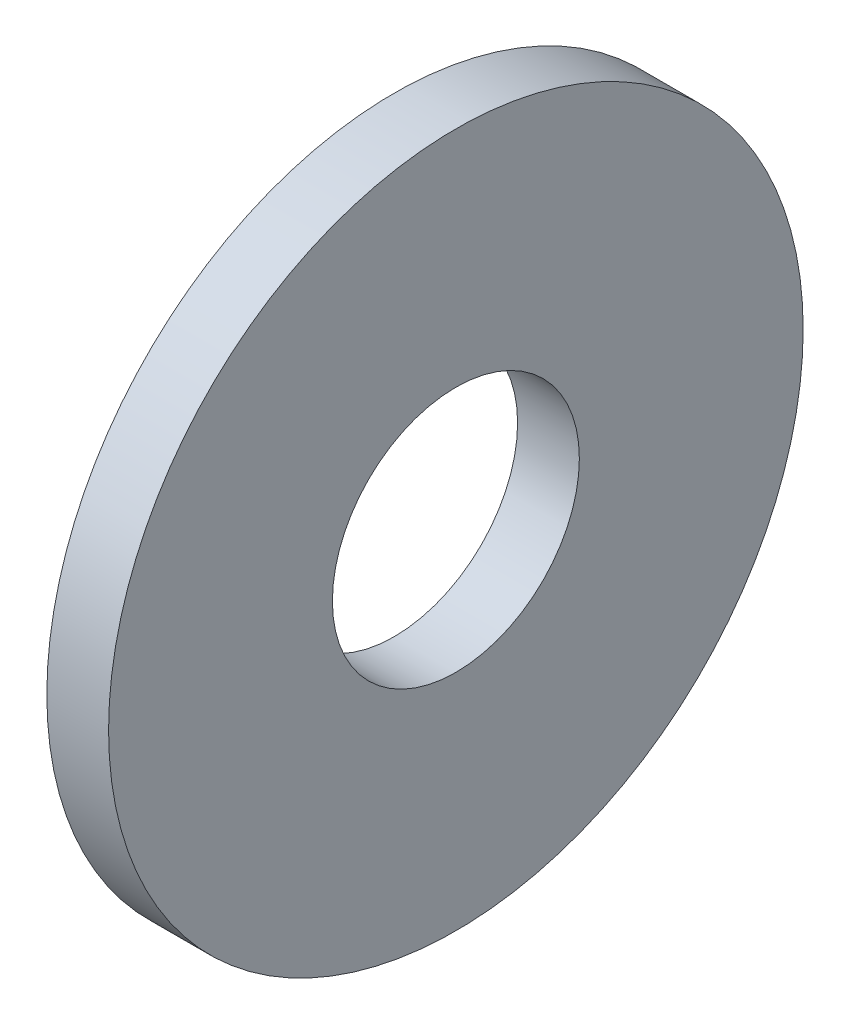
SolidWorks part; units mm, degrees
ref_plane "Plane1" through (0, 0, 0) normal (0, 0, 1) x (1, 0, 0)
ref_plane "Plane2" through (0, 0, 0) normal (0, 1, 0) x (1, 0, 0)
ref_plane "Plane3" through (0, 0, 0) normal (1, 0, 0) x (0, 0, -1)
sketch "Sketch1" plane through (0, 0, 0) normal (0, 0, 1) x (1, 0, 0)
  line L0 (-34.925, 0) -> (9.525, 0) construction
  line L1 (0, 1.6) -> (0, 4.5)
  line L2 (0, 4.5) -> (-0.8, 4.5)
  line L3 (-0.8, 4.5) -> (-0.8, 1.6)
  line L4 (-0.8, 1.6) -> (0, 1.6)
  dimension "Thickness" = 0.8
  dimension "Inside_dia" = 3.2
  dimension "Outside_dia" = 9
revolve "Base-Revolve" add sketch "Sketch1" angle 360 about L0
